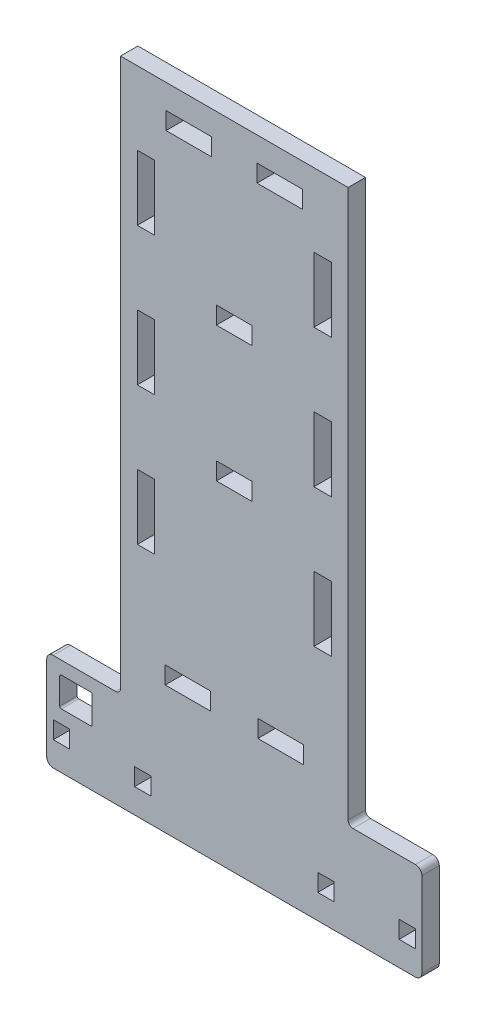
SolidWorks part; units mm, degrees
ref_plane "Front Plane" through (0, 0, 0) normal (0, 0, 1) x (1, 0, 0)
ref_plane "Top Plane" through (0, 0, 0) normal (0, 1, 0) x (1, 0, 0)
ref_plane "Right Plane" through (0, 0, 0) normal (1, 0, 0) x (0, 0, -1)
sketch "Model" plane through (0, 0, 0) normal (0, 0, 1) x (1, 0, 0)
  line L0 (0, 0) -> (0, 200) construction
  line L1 (-55.695, 30) -> (-36.5, 30)
  line L2 (-57.695, 28) -> (-57.695, 2)
  line L3 (-55.695, 0) -> (55.695, 0)
  line L4 (57.695, 28) -> (57.695, 2)
  line L5 (50.675, 12.9) -> (50.675, 7.55)
  line L6 (-55.675, 12.9) -> (-50.675, 12.9)
  line L7 (7.25, 44.7) -> (7.25, 39.35)
  line L8 (-35, 31.5) -> (-35, 200)
  line L9 (-35, 200) -> (35, 200)
  line L10 (35, 31.5) -> (35, 200)
  line L11 (36.5, 30) -> (55.695, 30)
  line L12 (-5.5, 143.075) -> (5.5, 143.075)
  line L13 (-5.5, 143.075) -> (-5.5, 148.425)
  line L14 (-5.5, 148.425) -> (5.5, 148.425)
  line L15 (5.5, 143.075) -> (5.5, 148.425)
  line L16 (-5.5, 143.075) -> (5.5, 148.425) construction
  line L17 (-5.5, 148.425) -> (5.5, 143.075) construction
  line L18 (-5.5, 101.575) -> (5.5, 101.575)
  line L19 (-5.5, 101.575) -> (-5.5, 106.925)
  line L20 (-5.5, 106.925) -> (5.5, 106.925)
  line L21 (5.5, 101.575) -> (5.5, 106.925)
  line L22 (-5.5, 101.575) -> (5.5, 106.925) construction
  line L23 (-5.5, 106.925) -> (5.5, 101.575) construction
  line L24 (-21, 192.5) -> (-7, 192.5)
  line L25 (-21, 192.5) -> (-21, 187.15)
  line L26 (-21, 187.15) -> (-7, 187.15)
  line L27 (-7, 192.5) -> (-7, 187.15)
  line L28 (-29.83, 177.5) -> (-24.48, 177.5)
  line L29 (-29.83, 177.5) -> (-29.83, 157.5)
  line L30 (-29.83, 157.5) -> (-24.48, 157.5)
  line L31 (-24.48, 177.5) -> (-24.48, 157.5)
  line L32 (-29.83, 135) -> (-24.48, 135)
  line L33 (-29.83, 135) -> (-29.83, 115)
  line L34 (-29.83, 115) -> (-24.48, 115)
  line L35 (-24.48, 135) -> (-24.48, 115)
  line L36 (-29.83, 92.5) -> (-24.48, 92.5)
  line L37 (-29.83, 92.5) -> (-29.83, 72.5)
  line L38 (-29.83, 72.5) -> (-24.48, 72.5)
  line L39 (-24.48, 92.5) -> (-24.48, 72.5)
  line L40 (-21.25, 44.7) -> (-7.25, 44.7)
  line L41 (-21.25, 44.7) -> (-21.25, 39.35)
  line L42 (-21.25, 39.35) -> (-7.25, 39.35)
  line L43 (-7.25, 44.7) -> (-7.25, 39.35)
  line L44 (21.25, 39.35) -> (7.25, 39.35)
  line L45 (21.25, 44.7) -> (21.25, 39.35)
  line L46 (21.25, 44.7) -> (7.25, 44.7)
  line L47 (24.48, 92.5) -> (24.48, 72.5)
  line L48 (29.83, 72.5) -> (24.48, 72.5)
  line L49 (29.83, 92.5) -> (29.83, 72.5)
  line L50 (29.83, 92.5) -> (24.48, 92.5)
  line L51 (24.48, 135) -> (24.48, 115)
  line L52 (29.83, 115) -> (24.48, 115)
  line L53 (29.83, 135) -> (29.83, 115)
  line L54 (29.83, 135) -> (24.48, 135)
  line L55 (24.48, 177.5) -> (24.48, 157.5)
  line L56 (29.83, 157.5) -> (24.48, 157.5)
  line L57 (29.83, 177.5) -> (29.83, 157.5)
  line L58 (29.83, 177.5) -> (24.48, 177.5)
  line L59 (7, 192.5) -> (7, 187.15)
  line L60 (21, 187.15) -> (7, 187.15)
  line L61 (21, 192.5) -> (21, 187.15)
  line L62 (21, 192.5) -> (7, 192.5)
  line L63 (-55.675, 12.9) -> (-55.675, 7.55)
  line L64 (-55.675, 7.55) -> (-50.675, 7.55)
  line L65 (-50.675, 12.9) -> (-50.675, 7.55)
  line L66 (-30.675, 12.9) -> (-25.675, 12.9)
  line L67 (-30.675, 12.9) -> (-30.675, 7.55)
  line L68 (-30.675, 7.55) -> (-25.675, 7.55)
  line L69 (-25.675, 12.9) -> (-25.675, 7.55)
  line L70 (-53.195, 26) -> (-44.195, 26)
  line L71 (-53.695, 25.5) -> (-53.695, 17.5)
  line L72 (-53.195, 17) -> (-44.195, 17)
  line L73 (-43.695, 25.5) -> (-43.695, 17.5)
  line L74 (55.675, 7.55) -> (50.675, 7.55)
  line L75 (55.675, 12.9) -> (55.675, 7.55)
  line L76 (55.675, 12.9) -> (50.675, 12.9)
  line L77 (25.675, 12.9) -> (25.675, 7.55)
  line L78 (30.675, 7.55) -> (25.675, 7.55)
  line L79 (30.675, 12.9) -> (30.675, 7.55)
  line L80 (30.675, 12.9) -> (25.675, 12.9)
  arc A0 (-36.5, 30) -> (-35, 31.5) centre (-36.5, 31.5) ccw
  arc A1 (-55.695, 30) -> (-57.695, 28) centre (-55.695, 28) ccw
  arc A2 (-57.695, 2) -> (-55.695, 0) centre (-55.695, 2) ccw
  arc A3 (36.5, 30) -> (35, 31.5) centre (36.5, 31.5) cw
  arc A4 (-43.695, 25.5) -> (-44.195, 26) centre (-44.195, 25.5) ccw
  arc A5 (-53.195, 26) -> (-53.695, 25.5) centre (-53.195, 25.5) ccw
  arc A6 (-44.195, 17) -> (-43.695, 17.5) centre (-44.195, 17.5) ccw
  arc A7 (-53.695, 17.5) -> (-53.195, 17) centre (-53.195, 17.5) ccw
  arc A8 (57.695, 28) -> (55.695, 30) centre (55.695, 28) ccw
  arc A9 (55.695, 0) -> (57.695, 2) centre (55.695, 2) ccw
  point P11 (0, 145.75)
  point P12 (0, 200)
  point P17 (0, 104.25)
  dimension "D55" = 3
  dimension "D59" = 4
  dimension "D84" = 1
  dimension "D16" = 70
  dimension "D17" = 5.35
  dimension "D18" = 5.35
  dimension "D20" = 14
  dimension "D21" = 7.5
  dimension "D28" = 14
  dimension "D29" = 5.35
  dimension "D33" = 20
  dimension "D34" = 5.17
  dimension "D35" = 22.5
  dimension "D37" = 5.35
  dimension "D39" = 22.5
  dimension "D41" = 22.5
  dimension "D43" = 5.35
  dimension "D45" = 13.75
  dimension "D47" = 9.35
  dimension "D49" = 5.35
  dimension "D52" = 11
  dimension "D53" = 51.575
  dimension "D54" = 36.15
  dimension "D13" = 170
  dimension "D9" = 30
  dimension "D12" = 115.39
  dimension "D65" = 5.35
  dimension "D66" = 5
  dimension "D69" = 2.02
  dimension "D70" = 20
  dimension "D74" = 7.55
  dimension "D85" = 10
  dimension "D86" = 9
  dimension "D88" = 4
  dimension "D89" = 4
extrude "Boss-Extrude1" add sketch "Model" along normal blind 5.35
equation "\"mdfthick\"=5.35"
equation "\"D18@Model\"=\"mdfthick\""
equation "\"D29@Model\"=\"mdfthick\""
equation "\"D37@Model\"=\"mdfthick\""
equation "\"D43@Model\"=\"mdfthick\""
equation "\"D17@Model\"=\"mdfthick\""
equation "\"D49@Model\"=\"mdfthick\""
equation "\"D65@Model\"=\"mdfthick\""
equation "\"D1@Boss-Extrude1\"=\"mdfthick\""
